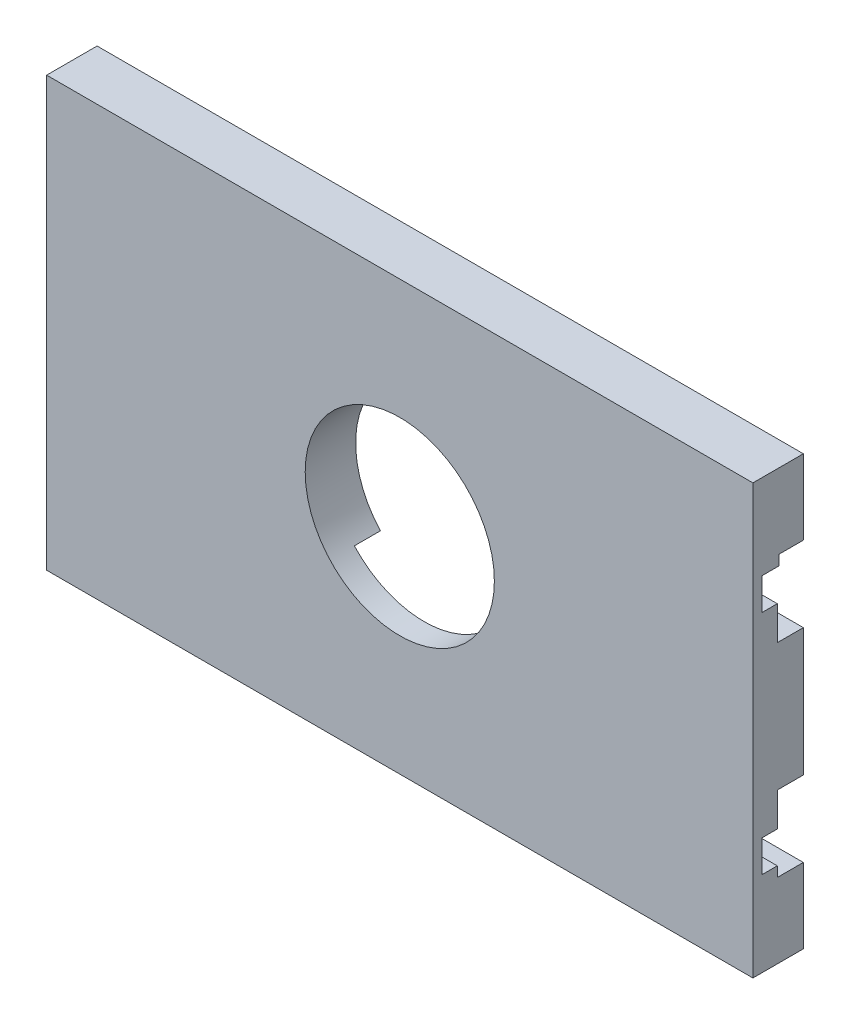
SolidWorks part; units mm, degrees
ref_plane "Front Plane" through (0, 0, 0) normal (0, 0, 1) x (1, 0, 0)
ref_plane "Top Plane" through (0, 0, 0) normal (0, 1, 0) x (1, 0, 0)
ref_plane "Right Plane" through (0, 0, 0) normal (1, 0, 0) x (0, 0, -1)
sketch "Sketch1" plane through (0, 0, 0) normal (1, 0, 0) x (0, 0, -1)
  line L0 (5, 27.66) -> (0.16, 27.66)
  line L1 (-5, -42.5) -> (5, -42.5)
  line L2 (-5, -42.5) -> (-5, 42.5)
  line L3 (-5, 42.5) -> (5, 42.5)
  line L4 (5, -42.5) -> (5, 42.5)
  line L5 (-5, -42.5) -> (5, 42.5) construction
  line L6 (-5, 42.5) -> (5, -42.5) construction
  line L7 (0.16, 27.66) -> (0.16, 25.66)
  line L8 (0.16, 25.66) -> (-3.16, 25.66)
  line L9 (-3.16, 25.66) -> (-3.16, 19.34)
  line L12 (-3.16, 19.34) -> (-0.16, 19.34)
  line L13 (-0.16, 19.34) -> (-0.16, 12.6506)
  line L14 (-0.16, 12.6506) -> (5, 12.6506)
  line L16 (5, 12.6506) -> (5, 27.66)
  line L17 (5, -27.66) -> (-0.16, -27.66)
  line L18 (-0.16, -27.66) -> (-0.16, -25.66)
  line L19 (-0.16, -25.66) -> (-3.16, -25.66)
  line L20 (-3.16, -19.34) -> (-3.16, -25.66)
  line L21 (-3.16, -19.34) -> (-0.16, -19.34)
  line L22 (-0.16, -19.34) -> (-0.16, -12.6506)
  line L23 (-0.16, -12.6506) -> (5, -12.6506)
  point P0 (0, 0)
  point P42 (2.42, -27.66)
  dimension "D1" = 85
  dimension "D2" = 10
  dimension "D3" = 5.16
  dimension "D4" = 2
  dimension "D5" = 3
  dimension "D6" = 6.32
  dimension "D7" = 3
  dimension "D8" = 6.6894
  dimension "D9" = 5.16
  dimension "D10" = 14.84
  dimension "D11" = 8.16
  dimension "D12" = 5.16
  dimension "D13" = 6.6894
  dimension "D14" = 6.32
  dimension "D15" = 2
  dimension "D16" = 4.84
  dimension "D17" = 14.84
  dimension "D18" = 8.16
  dimension "D19" = 3.32
  dimension "D20" = 3
extrude "Boss-Extrude1" add sketch "Sketch1" along normal blind 140 contours L22 L23 L4 L14 L13 L12 L9 L8 L7 L0 L3 L2 L1 L17 L18 L19 L20 L21
sketch "Sketch2" plane through (0, 0, 5) normal (0, 0, 1) x (1, 0, 0)
  line L0 (140, -42.5) -> (140, 42.5) construction
  line L1 (140, -42.5) -> (0, -42.5) construction
  circle A0 centre (70, 0) radius 18.75
  dimension "D1" = 37.5
  dimension "D2" = 70
  dimension "D3" = 42.5
extrude "Cut-Extrude1" cut sketch "Sketch2" against normal through all
